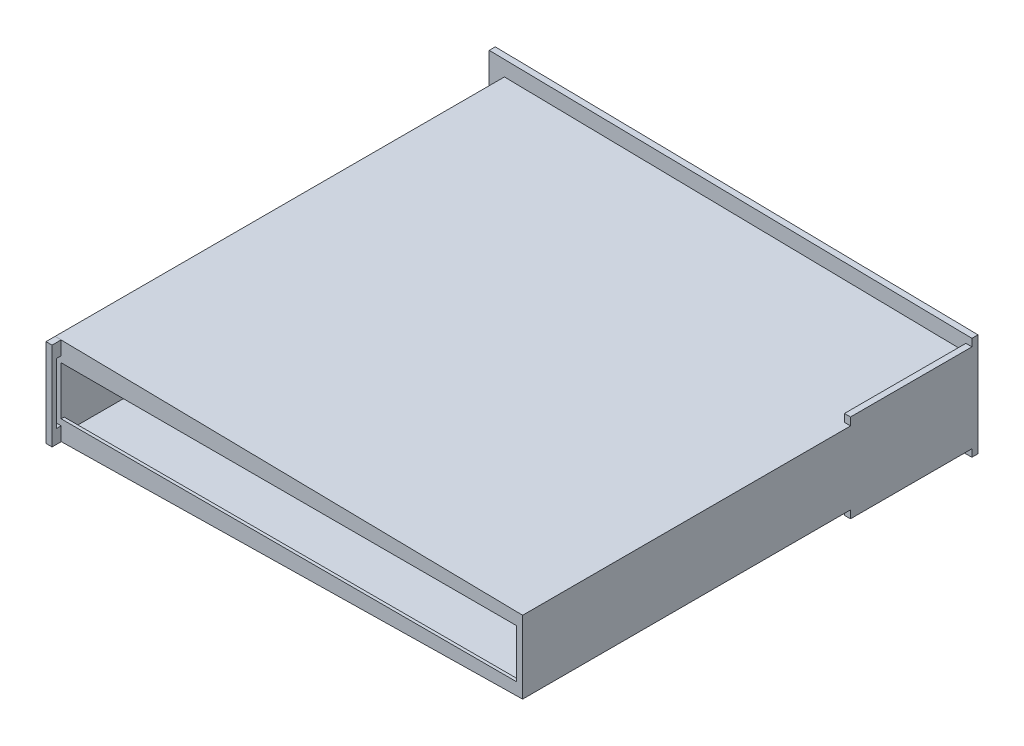
SolidWorks part; units mm, degrees
ref_plane "Front Plane" through (0, 0, 0) normal (0, 0, 1) x (1, 0, 0)
ref_plane "Top Plane" through (0, 0, 0) normal (0, 1, 0) x (1, 0, 0)
ref_plane "Right Plane" through (0, 0, 0) normal (1, 0, 0) x (0, 0, -1)
sketch "Sketch1" plane through (0, 0, 0) normal (0, 0, 1) x (1, 0, 0)
  line L0 (0, 25) -> (0, 0)
  line L1 (0, 0) -> (150, 2.5)
  line L2 (150, 2.5) -> (150, 22.5)
  line L3 (150, 22.5) -> (0, 25)
  line L4 (0, 12.5) -> (103.6749, 12.5) construction
  line L5 (-2, 27.0336) -> (-2, -2.0336)
  line L6 (-2, -2.0336) -> (152, 0.5331)
  line L7 (152, 0.5331) -> (152, 24.4669)
  line L8 (152, 24.4669) -> (-2, 27.0336)
  line L9 (0, 10.5) -> (103.6749, 10.5) construction
  point P8 (150, 12.5)
  dimension "D1" = 150
  dimension "D2" = 25
  dimension "D3" = 20
  dimension "D4" = 2
extrude "Boss-Extrude1" add sketch "Sketch1" along normal blind 150 contours L7 L8 L5 L6 L3 L2 L1 L0
sketch "Sketch2" plane through (0, 0, 150) normal (0, 0, 1) x (1, 0, 0)
  line L0 (3, 24.95) -> (3, 19.95)
  line L1 (150, 22.5) -> (0, 25) construction
  line L2 (3, 19.95) -> (5, 19.95)
  line L3 (5, 19.95) -> (5, 24.9167)
  line L4 (5, 24.9167) -> (3, 24.95)
  line L5 (0, 25) -> (0, 0) construction
  line L6 (0, 12.5) -> (90.911, 12.5) construction
  line L7 (5, 0.0833) -> (3, 0.05)
  line L8 (5, 5.05) -> (5, 0.0833)
  line L9 (3, 5.05) -> (5, 5.05)
  line L10 (3, 0.05) -> (3, 5.05)
  dimension "D1" = 5
  dimension "D2" = 2
  dimension "D3" = 3
extrude "Boss-Extrude2" [suppressed] add sketch "Sketch2" against normal blind 150 separate body
sketch "Sketch3" plane through (0, 0, 150) normal (0, 0, 1) x (1, 0, 0)
  line L0 (150, 20.5) -> (0, 20.5)
  line L1 (150, 2.5) -> (150, 22.5) construction
  line L2 (0, 25) -> (0, 0) construction
  line L3 (0, 20.5) -> (0, 4.5)
  line L4 (0, 4.5) -> (150, 4.5)
  line L6 (0, 20.5) -> (0, 25)
  line L7 (0, 25) -> (150, 22.5)
  line L8 (150, 22.5) -> (150, 20.5)
  line L9 (0, 4.5) -> (0, 0)
  line L10 (0, 0) -> (150, 2.5)
  line L11 (150, 2.5) -> (150, 4.5)
  line M9 (0, 25) -> (150, 22.5)
  line M10 (150, 22.5) -> (150, 2.5)
  line M11 (150, 2.5) -> (0, 0)
  line M12 (0, 0) -> (0, 25)
  dimension "D1" = 2
  dimension "D2" = 2
extrude "Boss-Extrude3" add sketch "Sketch3" against normal blind 1 separate body contours L0 M10 M9 M12 | L4 M12 M11 M10
ref_plane "Plane1" through (0, 0, 148) normal (0, 0, -1) x (-1, 0, 0)
sketch "Sketch4" plane through (0, 0, 148) normal (0, 0, -1) x (-1, 0, 0)
  line L0 (-150, 20.5) -> (0, 20.5) construction
  line L1 (0, 20.5) -> (0, 25) construction
  line L2 (0, 25) -> (-150, 22.5) construction
  line L3 (-150, 22.5) -> (-150, 20.5) construction
  line L4 (0, 4.5) -> (-150, 4.5) construction
  line L5 (-150, 4.5) -> (-150, 2.5) construction
  line L6 (-150, 2.5) -> (0, 0) construction
  line L7 (0, 0) -> (0, 4.5) construction
  line L8 (-150, 20.5) -> (0, 20.5)
  line L9 (0, 20.5) -> (0, 25)
  line L10 (0, 25) -> (-150, 22.5)
  line L11 (-150, 22.5) -> (-150, 20.5)
  line L12 (0, 4.5) -> (-150, 4.5)
  line L13 (-150, 4.5) -> (-150, 2.5)
  line L14 (-150, 2.5) -> (0, 0)
  line L15 (0, 0) -> (0, 4.5)
extrude "Boss-Extrude4" [suppressed] add sketch "Sketch4" along normal blind 1
sketch "Sketch6" plane through (-2, 0, 0) normal (-1, 0, 0) x (0, 0, 1)
  line L6 (150, 22.5) -> (151.5, 22.5)
  line L9 (151.5, 22.5) -> (151.5, 2.5)
  line L14 (151.5, 2.5) -> (150, 2.5)
  line L15 (150, -2.0336) -> (153, -2.0336)
  line L16 (153, -2.0336) -> (153, 27.0336)
  line L17 (153, 27.0336) -> (150, 27.0336)
  line L18 (150, 27.0336) -> (150, 22.5)
  line L19 (150, 2.5) -> (150, -2.0336)
  line L20 (150, 27.0336) -> (0, 27.0336) construction
  line L21 (150, 27.0336) -> (150, -2.0336) construction
  dimension "D1" = 3
  dimension "D2" = 1.5
extrude "Boss-Extrude5" add sketch "Sketch6" against normal blind 2
sketch "Sketch7" plane through (0, 0, 0) normal (0, 0, -1) x (-1, 0, 0)
  line L1 (-152, -4.4676) -> (7, -7.1176)
  line L2 (7, -7.1176) -> (7, 32.1176)
  line L3 (7, 32.1176) -> (-152, 29.4676)
  line L4 (-152, 24.4669) -> (-152, 0.5331)
  line L5 (-152, 0.5331) -> (2, -2.0336)
  line L6 (2, -2.0336) -> (2, 27.0336)
  line L7 (2, 27.0336) -> (-152, 24.4669)
  line L8 (-152, 29.4676) -> (-152, 24.4669)
  line L9 (-152, 0.5331) -> (2, -2.0336)
  line L10 (2, -2.0336) -> (2, 27.0336)
  line L11 (2, 27.0336) -> (-152, 24.4669)
  line L12 (-152, 24.4669) -> (-152, 0.5331) construction
  line L13 (-152, 0.5331) -> (-152, -4.4676)
  line L14 (7, 32.1176) -> (-157, 29.3843) construction
  line L15 (-157, -4.3843) -> (7, -7.1176) construction
  line L16 (-157, 29.3843) -> (-157, -4.3843) construction
  dimension "D1" = 0
  dimension "D2" = 5
extrude "Boss-Extrude6" add sketch "Sketch7" against normal blind 2
sketch "Sketch8" plane through (152, 0, 0) normal (1, 0, 0) x (0, 0, -1)
  line L0 (-2, 24.4669) -> (-42, 24.4669)
  line L1 (-150, 24.4669) -> (-2, 24.4669) construction
  line L2 (-42, 24.4669) -> (-42, 27.0336)
  line L3 (-150, 27.0336) -> (-2, 27.0336) construction
  line L4 (-42, 27.0336) -> (-2, 27.0336)
  line L5 (-2, 27.0336) -> (-2, 24.4669) construction
  line L6 (-2, 27.0336) -> (-2, 24.4669)
  line L7 (0, 12.5) -> (-84.6391, 12.5) construction
  line L9 (-2, -2.0336) -> (-2, 0.5331)
  line L10 (-42, -2.0336) -> (-2, -2.0336)
  line L11 (-42, 0.5331) -> (-42, -2.0336)
  line L12 (-2, 0.5331) -> (-42, 0.5331)
  line L13 (0, -4.4676) -> (0, 29.4676) construction
  dimension "D1" = 40
extrude "Boss-Extrude7" add sketch "Sketch8" against normal blind 2
